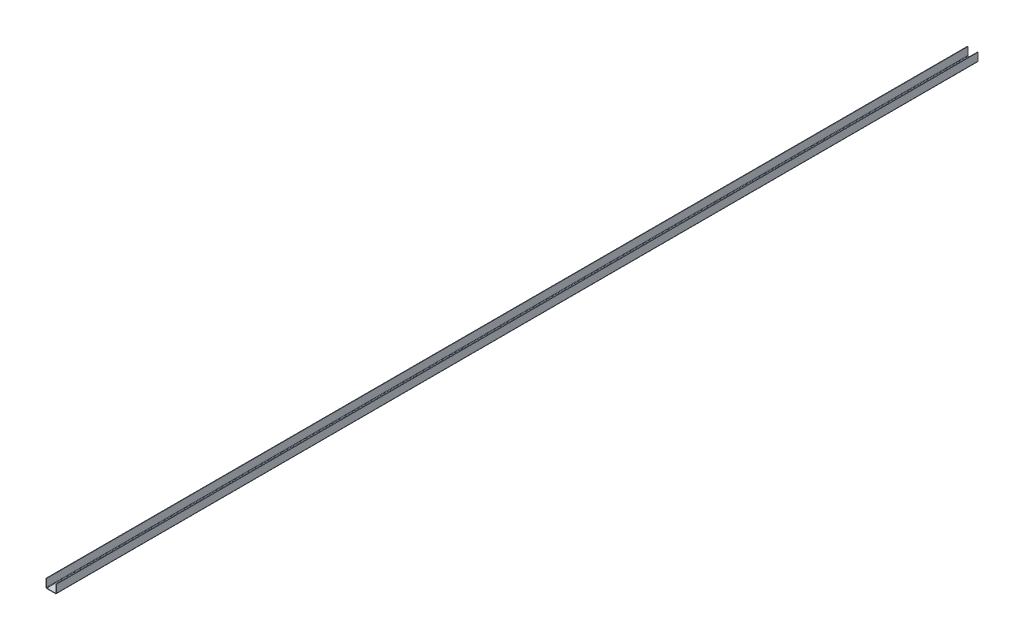
SolidWorks part; units mm, degrees
material "AISI 304"
ref_plane "Front Plane" through (0, 0, 0) normal (0, 0, 1) x (1, 0, 0)
ref_plane "Top Plane" through (0, 0, 0) normal (0, 1, 0) x (1, 0, 0)
ref_plane "Right Plane" through (0, 0, 0) normal (1, 0, 0) x (0, 0, -1)
sketch "Sketch1" plane through (0, 0, 0) normal (0, 0, 1) x (1, 0, 0)
  line L0 (11.2673, 18.1584) -> (11.2673, -6.8416)
  line L1 (8.2673, -9.8416) -> (-19.7327, -9.8416)
  line L2 (-22.7327, -6.8416) -> (-22.7327, 18.1584)
  arc A0 (11.2673, -6.8416) -> (8.2673, -9.8416) centre (8.2673, -6.8416) cw
  arc A1 (-19.7327, -9.8416) -> (-22.7327, -6.8416) centre (-19.7327, -6.8416) cw
  point P6 (11.2673, -9.8416)
  point P9 (-22.7327, -9.8416)
  dimension "D4" = 3
  dimension "D1" = 28
  dimension "D2" = 28
  dimension "D3" = 34
extrude "Extrude-Thin1" add sketch "Sketch1" along normal blind 2997 thin
sketch "Sketch2" plane through (0, -8.3416, 0) normal (0, 1, 0) x (1, 0, 0)
  line L0 (8.2673, -2997) -> (-19.7327, -2997) construction
  line L2 (11.2673, -2997) -> (11.2673, 0) construction
  circle A0 centre (-5.7327, -2498.5) radius 3.25
  dimension "D1" = 498.5
  dimension "D3" = 6.5
  dimension "D2" = 17
extrude "Cut-Extrude1" cut sketch "Sketch2" against normal through all
pattern_linear "LPattern1" count 3 spacing 1000 along (0, 0, -1) of "Cut-Extrude1"
